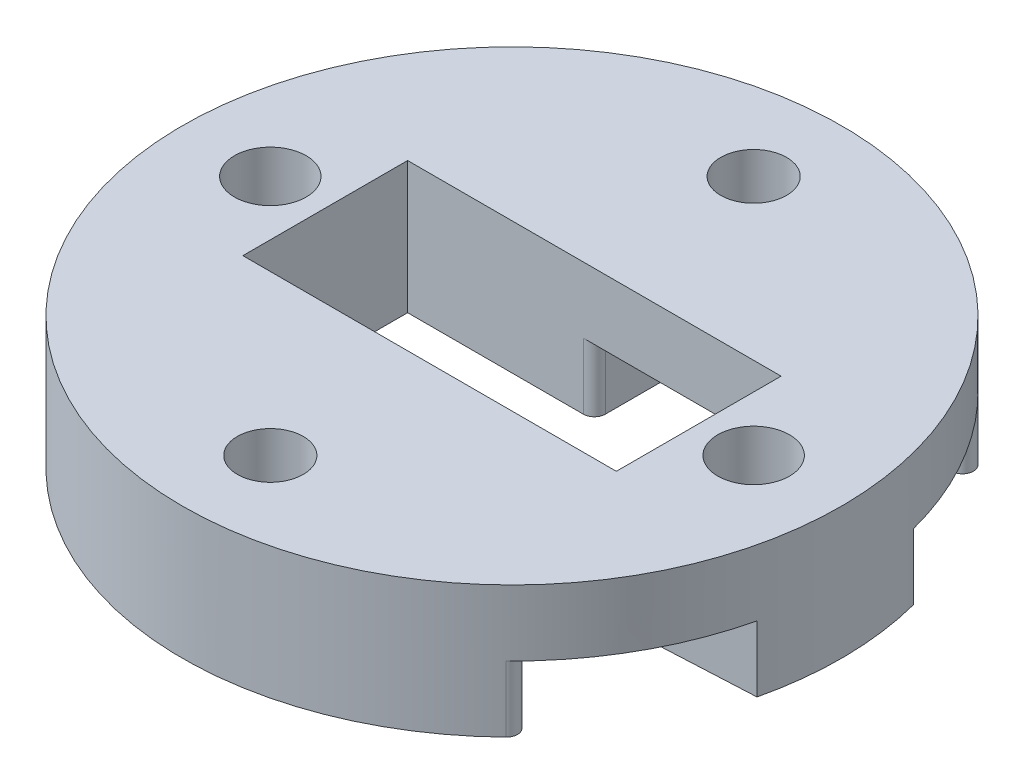
SolidWorks part; units mm, degrees
ref_plane "Front Plane" through (0, 0, 0) normal (0, 0, 1) x (1, 0, 0)
ref_plane "Top Plane" through (0, 0, 0) normal (0, 1, 0) x (1, 0, 0)
ref_plane "Right Plane" through (0, 0, 0) normal (1, 0, 0) x (0, 0, -1)
sketch "Sketch1" plane through (0, 0, 0) normal (0, 1, 0) x (1, 0, 0)
  line L1 (30, 0) -> (-30, 0) construction
  line L2 (0, 0) -> (0, 30) construction
  line L3 (0, 0) -> (0, -30) construction
  line L4 (-17, 7.5) -> (17, 7.5)
  line L5 (-17, 7.5) -> (-17, -7.5)
  line L6 (-17, -7.5) -> (17, -7.5)
  line L7 (17, 7.5) -> (17, -7.5)
  circle A0 centre (0, 0) radius 30
  circle A1 centre (-22, 0) radius 3.2653
  circle A2 centre (22, 0) radius 3.2653
  circle A3 centre (0, 22) radius 3
  circle A4 centre (0, -22) radius 3
  dimension "D1" = 8
  dimension "D3" = 8
  dimension "D8" = 44
  dimension "D2" = 8
  dimension "D4" = 8
  dimension "D5" = 34
  dimension "D6" = 7.5
  dimension "D7" = 17
  dimension "D9" = 44
extrude "Boss-Extrude1" add sketch "Sketch1" along normal blind 6
sketch3d "3DSketch1" plane through (0, 0, 0) normal (0, 0, 1) x (1, 0, 0)
sketch "Sketch3" plane through (0, 0, 0) normal (0, -1, 0) x (1, 0, 0)
  line L0 (20.2524, -19.7567) -> (1, -19.7567)
  line L1 (0, -18.7567) -> (0, -8.5)
  line L2 (17, -7.5) -> (-17, -7.5) construction
  line L3 (-1, -7.5) -> (-16, -7.5)
  line L4 (-17, -6.5) -> (-17, 6.5)
  line L5 (-16, 7.5) -> (-1, 7.5)
  line L6 (-17, 7.5) -> (17, 7.5) construction
  line L7 (0, 8.5) -> (0, 18.7567)
  line L8 (1, 19.7567) -> (20.2524, 19.7567)
  line L10 (29.1979, 6.8907) -> (17, 7.5)
  line L11 (17, 7.5) -> (17, -7.5) construction
  line L12 (17, 7.5) -> (17, -7.5)
  line L13 (17, -7.5) -> (29.0474, -7.5)
  arc A0 (20.9508, -21.4724) -> (20.9508, 21.4724) centre (0, 0) cw
  circle A1 centre (0, 0) radius 30 construction
  arc A2 (1, 19.7567) -> (0, 18.7567) centre (1, 18.7567) ccw
  arc A3 (0, -18.7567) -> (1, -19.7567) centre (1, -18.7567) ccw
  arc A4 (20.9508, -21.4724) -> (20.2524, -19.7567) centre (20.2524, -20.7567) ccw
  arc A5 (20.9508, 21.4724) -> (20.2524, 19.7567) centre (20.2524, 20.7567) cw
  arc A6 (0, 8.5) -> (-1, 7.5) centre (-1, 8.5) cw
  arc A7 (-17, 6.5) -> (-16, 7.5) centre (-16, 6.5) cw
  arc A8 (-17, -6.5) -> (-16, -7.5) centre (-16, -6.5) ccw
  arc A9 (-1, -7.5) -> (0, -8.5) centre (-1, -8.5) cw
  arc A10 (29.1979, 6.8907) -> (29.0474, -7.5) centre (0, 0) ccw
  point P24 (22.5759, -19.7567)
  point P27 (22.5759, 19.7567)
  point P30 (0, 7.5)
  point P33 (-17, 7.5)
  point P36 (-17, -7.5)
  point P39 (0, -7.5)
  circle M2 centre (0, 22) radius 3
  circle M3 centre (0, -22) radius 3
  circle M4 centre (22, 0) radius 3.2653
  circle M5 centre (-22, 0) radius 3.2653
  circle M6 centre (0, 0) radius 30
  line M7 (-17, -7.5) -> (-17, 7.5)
  line M8 (-17, 7.5) -> (17, 7.5)
  line M9 (17, 7.5) -> (17, -7.5)
  line M10 (17, -7.5) -> (-17, -7.5)
  dimension "D1" = 1
  dimension "D2" = 1
  dimension "D3" = 1
  dimension "D4" = 1
  dimension "D5" = 1
  dimension "D6" = 1
  dimension "D7" = 1
  dimension "D8" = 1
extrude "Boss-Extrude3" add sketch "Sketch3" along normal blind 6 contours A9 A6 L7 A2 L8 A5 A4 L0 A3 L1 M10 M7 M8 M6 M3 M5 M2 | L13 L10 M9 M6 M4
